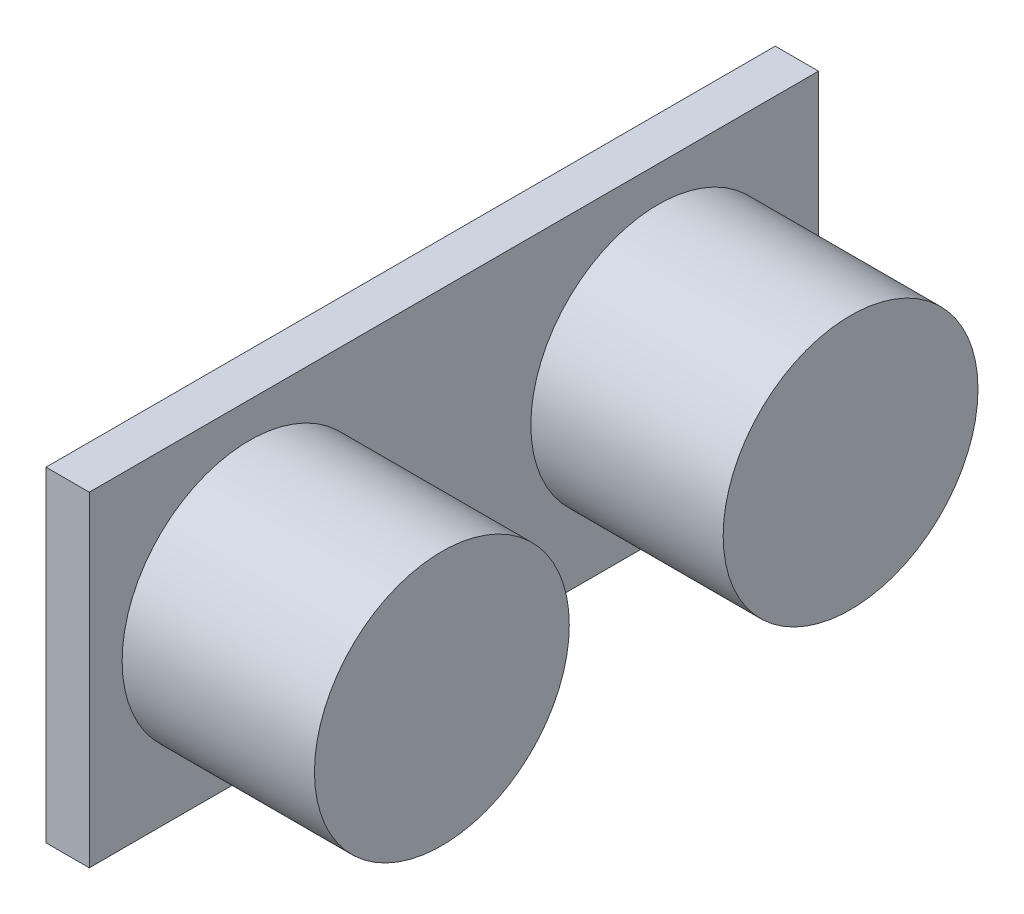
SolidWorks part; units mm, degrees
ref_plane "Front Plane" through (0, 0, 0) normal (0, 0, 1) x (1, 0, 0)
ref_plane "Top Plane" through (0, 0, 0) normal (0, 1, 0) x (1, 0, 0)
ref_plane "Right Plane" through (0, 0, 0) normal (1, 0, 0) x (0, 0, -1)
sketch "Sketch1" plane through (0, 0, 0) normal (1, 0, 0) x (0, 0, -1)
  line L1 (0, 0) -> (45.5, 0)
  line L2 (0, 0) -> (0, 20.3)
  line L3 (0, 20.3) -> (45.5, 20.3)
  line L4 (45.5, 0) -> (45.5, 20.3)
  dimension "D1" = 45.5
  dimension "D2" = 20.3
extrude "Boss-Extrude1" add sketch "Sketch1" along normal blind 2.7
sketch "Sketch2" plane through (2.7, 0, 0) normal (1, 0, 0) x (0, 0, -1)
  line L0 (0, 10.15) -> (45.5, 10.15) construction
  line L1 (0, 20.3) -> (0, 0) construction
  line L2 (45.5, 0) -> (45.5, 20.3) construction
  circle A0 centre (10, 10.15) radius 7.95
  circle A1 centre (35.5, 10.15) radius 7.95
  point P10 (35.8862, 10.15)
  point P11 (10.0676, 10.15)
  dimension "D3" = 15.9
  dimension "D1" = 10
  dimension "D2" = 10
extrude "Boss-Extrude2" add sketch "Sketch2" along normal blind 12
